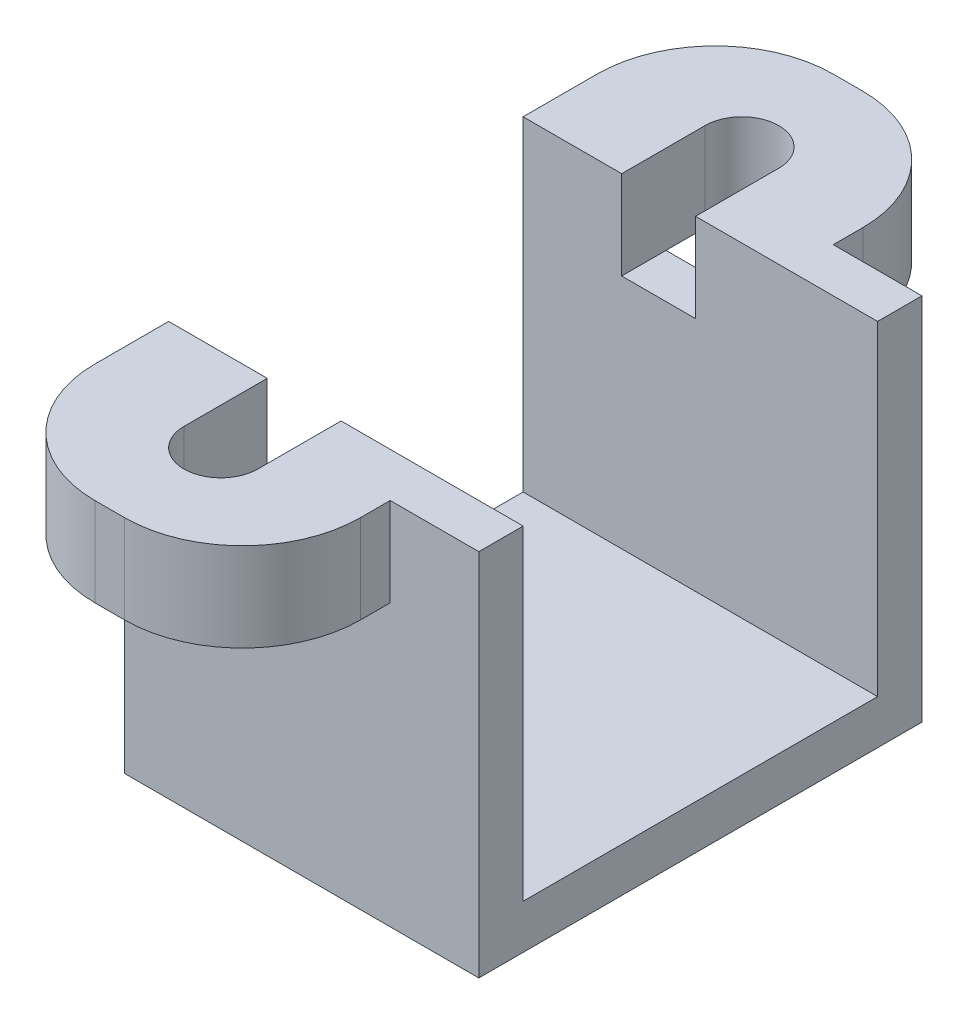
SolidWorks part; units mm, degrees
ref_plane "前视基准面" through (0, 0, 0) normal (0, 0, 1) x (1, 0, 0)
ref_plane "上视基准面" through (0, 0, 0) normal (0, 1, 0) x (1, 0, 0)
ref_plane "右视基准面" through (0, 0, 0) normal (1, 0, 0) x (0, 0, -1)
sketch "草图1" plane through (0, 0, 0) normal (0, 1, 0) x (1, 0, 0)
  line L1 (-6, 7.5) -> (6, 7.5)
  line L2 (-6, 7.5) -> (-6, -7.5)
  line L3 (-6, -7.5) -> (6, -7.5)
  line L4 (6, 7.5) -> (6, -7.5)
  line L5 (-6, 7.5) -> (6, -7.5) construction
  line L6 (-6, -7.5) -> (6, 7.5) construction
  point P0 (0, 0)
  dimension "D1" = 15
  dimension "D2" = 12
extrude "凸台-拉伸1" add sketch "草图1" along normal blind 1.5
sketch "草图2" plane through (0, 1.5, 0) normal (0, 1, 0) x (1, 0, 0)
  line L0 (6, -7.5) -> (6, 7.5) construction
  line L1 (-6, 7.5) -> (6, 7.5)
  line L2 (-6, 7.5) -> (-6, 6)
  line L3 (-6, 6) -> (6, 6)
  line L4 (6, 7.5) -> (6, 6)
  line L6 (-6, -7.5) -> (6, -7.5)
  line L7 (-6, -7.5) -> (-6, -6)
  line L8 (-6, -6) -> (6, -6)
  line L9 (6, -7.5) -> (6, -6)
  dimension "D1" = 1.5
  dimension "D2" = 1.5
extrude "凸台-拉伸2" add sketch "草图2" along normal blind 11
sketch "草图3" plane through (0, 12.5, 0) normal (0, 1, 0) x (1, 0, 0)
  line L0 (0, 0) -> (10.8149, 0) construction
  line L1 (-6, 6) -> (3, 6)
  line L2 (-6, 6) -> (-6, 12.5)
  line L3 (-6, 12.5) -> (3, 12.5)
  line L4 (3, 6) -> (3, 12.5)
  line L5 (3, -6) -> (3, -12.5)
  line L6 (-6, -12.5) -> (3, -12.5)
  line L7 (-6, -6) -> (-6, -12.5)
  line L8 (-6, -6) -> (3, -6)
  dimension "D1" = 9
  dimension "D2" = 6.5
extrude "凸台-拉伸3" add sketch "草图3" against normal blind 3
fillet "圆角1" radius 4 2 edges at (3, 11, -12.5) (-6, 11, -12.5)
sketch "草图4" plane through (0, 12.5, 0) normal (0, 1, 0) x (1, 0, 0)
  line L0 (-2.6632, 8.8193) -> (-2.6632, 6)
  line L1 (-6, 6) -> (6, 6) construction
  line L2 (-2.6632, 6) -> (-0.1632, 6)
  line L3 (-6, 6) -> (6, 6) construction
  line L4 (-0.1632, 6) -> (-0.1632, 8.8193)
  line L5 (0, 0) -> (9.058, 0) construction
  line L6 (-0.1632, -6) -> (-0.1632, -8.8193)
  line L7 (-2.6632, -6) -> (-0.1632, -6)
  line L8 (-2.6632, -8.8193) -> (-2.6632, -6)
  arc A0 (-0.1632, 8.8193) -> (-2.6632, 8.8193) centre (-1.4132, 8.8193) ccw
  arc A1 (-0.1632, -8.8193) -> (-2.6632, -8.8193) centre (-1.4132, -8.8193) cw
  dimension "D1" = 2.5
extrude "切除-拉伸1" cut sketch "草图4" against normal blind 3 and the other way through all
fillet "圆角2" radius 4 2 edges at (-6, 11, 12.5) (3, 11, 12.5)
